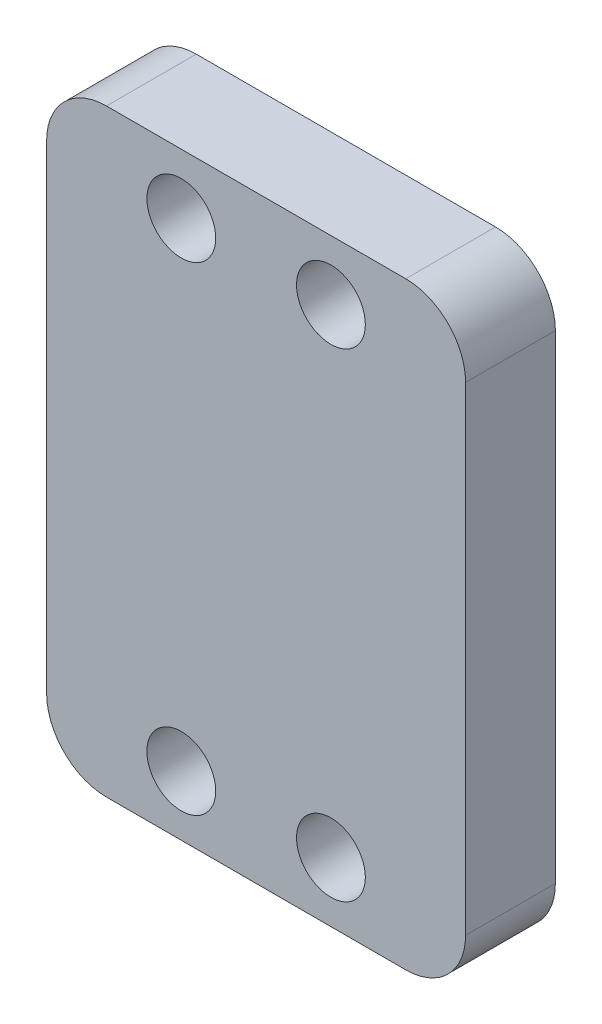
SolidWorks part; units mm, degrees
ref_plane "前视基准面" through (0, 0, 0) normal (0, 0, 1) x (1, 0, 0)
ref_plane "上视基准面" through (0, 0, 0) normal (0, 1, 0) x (1, 0, 0)
ref_plane "右视基准面" through (0, 0, 0) normal (1, 0, 0) x (0, 0, -1)
sketch "草图1" plane through (0, 0, 0) normal (0, 0, 1) x (1, 0, 0)
  line L1 (-7, -10) -> (7, -10)
  line L2 (-7, -10) -> (-7, 10)
  line L3 (-7, 10) -> (7, 10)
  line L4 (7, -10) -> (7, 10)
  line L5 (-7, -10) -> (7, 10) construction
  line L6 (-7, 10) -> (7, -10) construction
  point P0 (0, 0)
  dimension "D1" = 14
  dimension "D2" = 20
extrude "凸台-拉伸1" add sketch "草图1" along normal mid plane 3
sketch "草图2" plane through (0, 0, 1.5) normal (0, 0, 1) x (1, 0, 0)
  line L1 (-2.5, -8) -> (2.5, -8) construction
  line L2 (-2.5, -8) -> (-2.5, 8) construction
  line L3 (-2.5, 8) -> (2.5, 8) construction
  line L4 (2.5, -8) -> (2.5, 8) construction
  line L5 (-2.5, -8) -> (2.5, 8) construction
  line L6 (-2.5, 8) -> (2.5, -8) construction
  circle A1 centre (-2.5, 8) radius 1.15
  circle A2 centre (2.5, 8) radius 1.15
  circle A3 centre (-2.5, -8) radius 1.15
  circle A4 centre (2.5, -8) radius 1.15
  point P0 (0, 0)
  dimension "D1" = 2.3
  dimension "D3" = 5
  dimension "D2" = 16
extrude "切除-拉伸1" cut sketch "草图2" against normal through all
fillet "圆角1" radius 2 4 edges at (-7, -10, 0) (7, -10, 0) (7, 10, 0) (-7, 10, 0)
